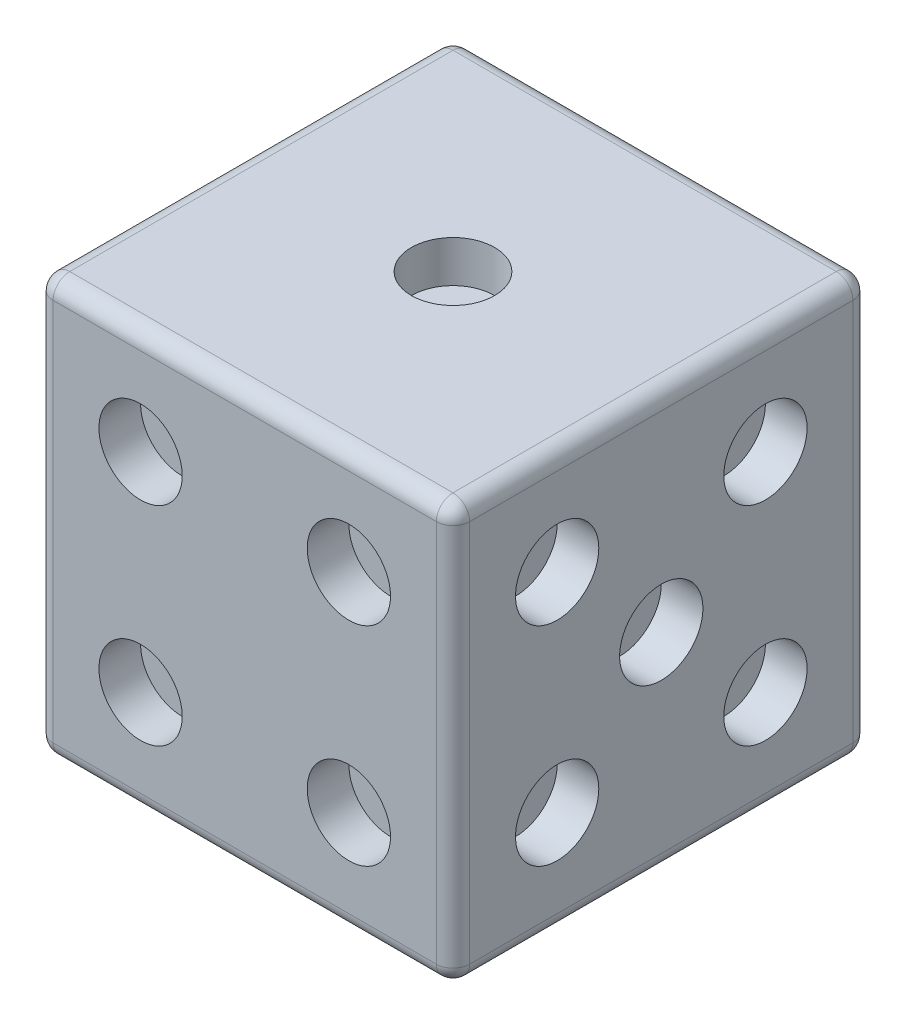
SolidWorks part; units mm, degrees
ref_plane "Alzado" through (0, 0, 0) normal (0, 0, 1) x (1, 0, 0)
ref_plane "Planta" through (0, 0, 0) normal (0, 1, 0) x (1, 0, 0)
ref_plane "Vista lateral" through (0, 0, 0) normal (1, 0, 0) x (0, 0, -1)
sketch "Croquis1" plane through (0, 0, 0) normal (0, 0, 1) x (1, 0, 0)
  line L1 (-50, -50) -> (50, -50)
  line L2 (-50, -50) -> (-50, 50)
  line L3 (-50, 50) -> (50, 50)
  line L4 (50, -50) -> (50, 50)
  line L5 (-50, -50) -> (50, 50) construction
  line L6 (-50, 50) -> (50, -50) construction
  point P0 (0, 0)
  dimension "D1" = 100
  dimension "D2" = 100
extrude "Saliente-Extruir1" add sketch "Croquis1" along normal blind 100
sketch "Croquis8" plane through (0, 50, 0) normal (0, 1, 0) x (1, 0, 0)
  circle A0 centre (0, -50) radius 10
  dimension "D1" = 20
extrude "Cortar-Extruir7" cut sketch "Croquis8" against normal blind 10 contours A0
sketch "Croquis9" plane through (0, 0, 100) normal (0, 0, 1) x (1, 0, 0)
  line L0 (-50, 50) -> (50, -50) construction
  line L1 (-50, -50) -> (50, 50) construction
  line L2 (50, 50) -> (50, 0)
  line L3 (50, -50) -> (50, 50) construction
  line L4 (50, 0) -> (0, 50) construction
  line L5 (50, 50) -> (-50, 50) construction
  line L6 (0, 50) -> (-50, 0) construction
  line L7 (-50, 50) -> (-50, -50) construction
  line L8 (-50, 0) -> (0, -50) construction
  line L9 (-50, -50) -> (50, -50) construction
  line L10 (0, -50) -> (50, 0) construction
  circle A0 centre (-25, 25) radius 10
  circle A1 centre (25, -25) radius 10
  circle A2 centre (25, 25) radius 10
  circle A3 centre (-25, -25) radius 10
  dimension "D1" = 20
sketch "Croquis10" plane through (0, -50, 0) normal (0, -1, 0) x (1, 0, 0)
  line L0 (-50, 100) -> (50, 0)
  circle A0 centre (-25, 75) radius 10
  circle A1 centre (0, 50) radius 10
  circle A2 centre (25, 25) radius 10
  point P4 (-25, 75)
  point P5 (0, 50)
  point P6 (25, 25)
  dimension "D1" = 20
extrude "Cortar-Extruir9" cut sketch "Croquis10" against normal blind 10 contours A0 | A1 | A2
sketch "Croquis11" plane through (0, 0, 0) normal (0, 0, -1) x (-1, 0, 0)
  line L0 (-50, -50) -> (50, 50) construction
  line L1 (50, 50) -> (-50, 50)
  line L2 (-50, 50) -> (50, -50) construction
  line L3 (50, -50) -> (0, -50)
  line L4 (50, -50) -> (-50, -50) construction
  line L5 (0, -50) -> (-50, 0) construction
  line L6 (-50, -50) -> (-50, 50) construction
  line L7 (-50, 0) -> (0, 50) construction
  line L8 (0, 50) -> (50, 0) construction
  line L9 (50, 50) -> (50, -50) construction
  line L10 (50, 0) -> (0, -50) construction
  circle A0 centre (-25, -25) radius 10
  circle A2 centre (25, 25) radius 10
  dimension "D1" = 20
extrude "Cortar-Extruir11" cut sketch "Croquis11" against normal blind 10 contours A0 | A2
extrude "Cortar-Extruir12" cut sketch "Croquis9" against normal blind 10 contours A3 | A0 | A1 | A2
sketch "Croquis12" plane through (50, 0, 0) normal (1, 0, 0) x (0, 0, -1)
  line L0 (0, -50) -> (-100, 50) construction
  line L1 (-100, 50) -> (-100, -50)
  line L2 (-100, -50) -> (0, 50) construction
  line L3 (0, 50) -> (0, 0)
  line L4 (0, -50) -> (0, 50) construction
  line L5 (0, 0) -> (-50, -50) construction
  line L6 (-100, -50) -> (0, -50) construction
  line L7 (-50, -50) -> (-100, 0) construction
  line L8 (-100, 0) -> (-50, 50) construction
  line L9 (-100, 50) -> (0, 50) construction
  line L10 (-50, 50) -> (0, 0) construction
  circle A0 centre (-25, -25) radius 10
  circle A1 centre (-50, 0) radius 10
  circle A2 centre (-75, -25) radius 10
  circle A3 centre (-75, 25) radius 10
  circle A4 centre (-25, 25) radius 10
  dimension "D1" = 20
extrude "Cortar-Extruir13" cut sketch "Croquis12" against normal blind 10 contours A4 | A3 | A1 | A2 | A0
sketch "Croquis13" plane through (-50, 0, 0) normal (-1, 0, 0) x (0, 0, 1)
  line L0 (0, 50) -> (50, 50)
  line L1 (100, 50) -> (0, 50) construction
  line L2 (25, 50) -> (25, -50) construction
  line L3 (100, -50) -> (0, -50) construction
  line L4 (25, -50) -> (74.9394, -50)
  line L5 (74.9394, -50) -> (74.9394, 50) construction
  circle A0 centre (25, 25) radius 10
  circle A1 centre (25, 0) radius 10
  circle A2 centre (25, -25) radius 10
  circle A3 centre (74.9394, 25) radius 10
  circle A4 centre (74.9394, 0) radius 10
  circle A5 centre (74.9394, -25) radius 10
  point P9 (25, 25)
  point P12 (25, 0)
  point P13 (25, -25)
  point P14 (74.9394, -25)
  point P15 (74.9394, 0)
  point P16 (74.9394, 25)
  dimension "D1" = 20
extrude "Cortar-Extruir14" cut sketch "Croquis13" against normal blind 10 contours A5 | A4 | A3 | A2 | A1 | A0
fillet "Redondeo2" radius 4 3 edges at (50, -50, 50) (0, -50, 100) (50, 0, 100)
fillet "Redondeo3" radius 4 12 edges at (-50, -48.8284, 98.8284) (-2, 50, 100) (48.8284, 50, 98.8284) (-2, -50, 0) (48.8284, -48.8284, 0) (-50, 50, 50) (-50, 0, 0) (0, 50, 0) (-50, 2, 100) (-50, -50, 48) (50, 50, 48) (50, 2, 0)
